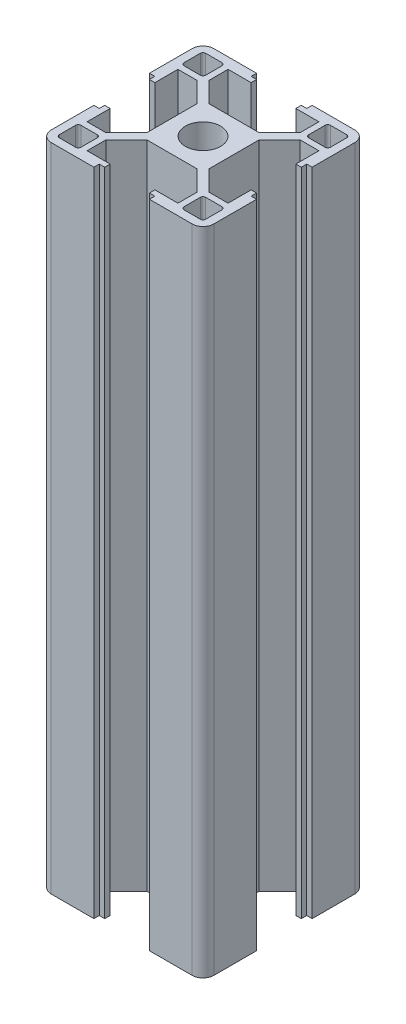
SolidWorks part; units mm, degrees
material "6061 Alloy"
ref_plane "Front Plane" through (0, 0, 0) normal (0, 0, 1) x (1, 0, 0)
ref_plane "Top Plane" through (0, 0, 0) normal (0, 1, 0) x (1, 0, 0)
ref_plane "Right Plane" through (0, 0, 0) normal (1, 0, 0) x (0, 0, -1)
sketch "Sketch1" plane through (0, 0, 0) normal (0, 1, 0) x (1, 0, 0)
  line L0 (-8.375, 13) -> (-4.125, 13)
  line L1 (-13, 15) -> (-4.125, 15)
  line L2 (-15, 13) -> (-15, 4.125)
  line L3 (-13, -15) -> (-4.125, -15)
  line L4 (15, 13) -> (15, 4.125)
  line L5 (-15, 15) -> (15, -15) construction
  line L6 (-15, -15) -> (15, 15) construction
  line L7 (-11.5, 11.5) -> (11.5, 11.5) construction
  line L8 (-11.5, 11.5) -> (-11.5, -11.5) construction
  line L9 (-11.5, -11.5) -> (11.5, -11.5) construction
  line L10 (11.5, 11.5) -> (11.5, -11.5) construction
  line L11 (-11.5, 11.5) -> (11.5, -11.5) construction
  line L12 (-11.5, -11.5) -> (11.5, 11.5) construction
  line L13 (-13.5, 13.5) -> (-9.5, 13.5)
  line L14 (-13.5, 13.5) -> (-13.5, 9.5)
  line L15 (-13.5, 9.5) -> (-9.5, 9.5)
  line L16 (-9.5, 13.5) -> (-9.5, 9.5)
  line L17 (-13.5, 13.5) -> (-9.5, 9.5) construction
  line L18 (-13.5, 9.5) -> (-9.5, 13.5) construction
  line L19 (13.5, 13.5) -> (9.5, 13.5)
  line L20 (13.5, 13.5) -> (13.5, 9.5)
  line L21 (13.5, 9.5) -> (9.5, 9.5)
  line L22 (9.5, 13.5) -> (9.5, 9.5)
  line L23 (13.5, 13.5) -> (9.5, 9.5) construction
  line L24 (13.5, 9.5) -> (9.5, 13.5) construction
  line L25 (13.5, -13.5) -> (9.5, -13.5)
  line L26 (13.5, -13.5) -> (13.5, -9.5)
  line L27 (13.5, -9.5) -> (9.5, -9.5)
  line L28 (9.5, -13.5) -> (9.5, -9.5)
  line L29 (13.5, -13.5) -> (9.5, -9.5) construction
  line L30 (13.5, -9.5) -> (9.5, -13.5) construction
  line L31 (-13.5, -13.5) -> (-9.5, -13.5)
  line L32 (-13.5, -13.5) -> (-13.5, -9.5)
  line L33 (-13.5, -9.5) -> (-9.5, -9.5)
  line L34 (-9.5, -13.5) -> (-9.5, -9.5)
  line L35 (-13.5, -13.5) -> (-9.5, -9.5) construction
  line L36 (-13.5, -9.5) -> (-9.5, -13.5) construction
  line L37 (0, 15) -> (0, 13) construction
  line L38 (-4.125, 15) -> (-4.125, 13)
  line L39 (4.125, 15) -> (4.125, 13)
  line L40 (4.125, 15) -> (13, 15)
  line L41 (-15, 15) -> (15, 15) construction
  line L42 (4.125, 13) -> (8.375, 13)
  line L43 (-15, 13) -> (15, 13) construction
  line L44 (8.375, 9.5064) -> (4.6186, 5.75)
  line L45 (-4.6186, -5.75) -> (4.6186, -5.75)
  line L46 (-8.375, 13) -> (-8.375, 9.5)
  line L47 (8.375, 13) -> (8.375, 9.5)
  line L48 (-8.375, 15) -> (-8.375, 13) construction
  line L49 (8.375, 15) -> (8.375, 13) construction
  line L50 (-5.75, -4.6186) -> (-5.75, 4.6186)
  line L51 (-4.6186, 5.75) -> (4.6186, 5.75)
  line L52 (5.75, -4.6186) -> (5.75, 4.6186)
  line L53 (-5.75, -5.75) -> (5.75, 5.75) construction
  line L54 (-5.75, 5.75) -> (5.75, -5.75) construction
  line L55 (-8.375, 9.5064) -> (-4.6186, 5.75)
  line L56 (-10.6314, 9.5) -> (-5.75, 4.6186)
  line L57 (-14.4343, 15.5657) -> (15.5657, -14.4343) construction
  line L58 (15, 4.125) -> (13, 4.125)
  line L59 (13, 8.375) -> (13, 4.125)
  line L60 (13, 8.375) -> (9.5, 8.375)
  line L61 (9.5064, 8.375) -> (5.75, 4.6186)
  line L62 (9.5064, -8.375) -> (5.75, -4.6186)
  line L63 (13, -8.375) -> (9.5, -8.375)
  line L64 (13, -4.125) -> (13, -8.375)
  line L65 (15, -4.125) -> (13, -4.125)
  line L66 (4.125, -15) -> (4.125, -13)
  line L67 (8.375, -13) -> (4.125, -13)
  line L68 (8.375, -13) -> (8.375, -9.5)
  line L69 (8.375, -9.5064) -> (4.6186, -5.75)
  line L70 (-8.375, -9.5064) -> (-4.6186, -5.75)
  line L71 (-8.375, -13) -> (-8.375, -9.5)
  line L72 (-4.125, -13) -> (-8.375, -13)
  line L73 (-4.125, -15) -> (-4.125, -13)
  line L74 (-15, -4.125) -> (-13, -4.125)
  line L75 (-13, -8.375) -> (-13, -4.125)
  line L76 (-13, -8.375) -> (-9.5, -8.375)
  line L77 (-9.5064, -8.375) -> (-5.75, -4.6186)
  line L78 (-9.5064, 8.375) -> (-5.75, 4.6186)
  line L79 (-13, 8.375) -> (-9.5, 8.375)
  line L80 (-13, 4.125) -> (-13, 8.375)
  line L81 (-15, 4.125) -> (-13, 4.125)
  line L82 (-15, -4.125) -> (-15, -13)
  line L83 (4.125, -15) -> (13, -15)
  line L84 (15, -4.125) -> (15, -13)
  circle A0 centre (0, 0) radius 3.25
  circle A1 centre (0, 0) radius 3.25
  circle A2 centre (0, 0) radius 3.25
  circle A3 centre (0, 0) radius 3.25
  arc A4 (-15, -13) -> (-13, -15) centre (-13, -13) ccw
  arc A5 (13, -15) -> (15, -13) centre (13, -13) ccw
  arc A6 (13, 15) -> (15, 13) centre (13, 13) cw
  arc A7 (-13, 15) -> (-15, 13) centre (-13, 13) ccw
  point P0 (0, 0)
  point P6 (0, 0)
  point P31 (0, 0)
  point P48 (-15.5657, 14.4343)
  point P49 (14.4343, -15.5657)
  point P60 (0, 5.75)
  point P102 (0, 0)
  dimension "D17" = 6.5
  dimension "D10" = 2
  dimension "D1" = 30
  dimension "D2" = 30
  dimension "D3" = 23
  dimension "D4" = 23
  dimension "D5" = 4
  dimension "D6" = 4
  dimension "D7" = 4
  dimension "D8" = 4
  dimension "D12" = 3.5
  dimension "D16" = 11.5
  dimension "D11" = 11.5
  dimension "D9" = 2
  dimension "D18" = 0.8
extrude "Boss-Extrude1" add sketch "Sketch1" along normal blind 120
sketch "Sketch2" plane through (0, 120, 0) normal (0, 1, 0) x (1, 0, 0)
  line L0 (15, 4.125) -> (14, 4.125)
  line L1 (-4.125, 15) -> (-5.125, 15)
  line L2 (-4.125, 15) -> (-4.125, 14)
  line L3 (-4.125, 14) -> (-5.125, 14)
  line L4 (-5.125, 15) -> (-5.125, 14)
  line L5 (4.125, 15) -> (5.125, 15)
  line L6 (4.125, 15) -> (4.125, 14)
  line L7 (4.125, 14) -> (5.125, 14)
  line L8 (5.125, 15) -> (5.125, 14)
  line L9 (15, 4.125) -> (15, 5.125)
  line L10 (15, 5.125) -> (14, 5.125)
  line L11 (14, 4.125) -> (14, 5.125)
  line L12 (15, -4.125) -> (14, -4.125)
  line L13 (15, -4.125) -> (15, -5.125)
  line L14 (15, -5.125) -> (14, -5.125)
  line L15 (14, -4.125) -> (14, -5.125)
  line L16 (4.125, -15) -> (4.125, -14)
  line L17 (4.125, -15) -> (5.125, -15)
  line L18 (5.125, -15) -> (5.125, -14)
  line L19 (4.125, -14) -> (5.125, -14)
  line L20 (-4.125, -15) -> (-4.125, -14)
  line L21 (-4.125, -15) -> (-5.125, -15)
  line L22 (-5.125, -15) -> (-5.125, -14)
  line L23 (-4.125, -14) -> (-5.125, -14)
  line L24 (-15, -4.125) -> (-14, -4.125)
  line L25 (-15, -4.125) -> (-15, -5.125)
  line L26 (-15, -5.125) -> (-14, -5.125)
  line L27 (-14, -4.125) -> (-14, -5.125)
  line L28 (-15, 4.125) -> (-14, 4.125)
  line L29 (-15, 4.125) -> (-15, 5.125)
  line L30 (-15, 5.125) -> (-14, 5.125)
  line L31 (-14, 4.125) -> (-14, 5.125)
  point P36 (0, 0)
  dimension "D1" = 1
  dimension "D2" = 1
  dimension "D3" = 1
  dimension "D4" = 1
  dimension "D5" = 4
extrude "Cut-Extrude1" cut sketch "Sketch2" against normal through all
fillet "Fillet1" radius 0.5 16 edges at (9.5, 60, 13.5) (-13.5, 60, 13.5) (-13.5, 60, -9.5) (9.5, 60, -9.5) (-13.5, 60, 9.5) (9.5, 60, 9.5) (9.5, 60, -13.5) (-13.5, 60, -13.5) (-9.5, 60, -13.5) (13.5, 60, -13.5) (13.5, 60, 9.5) (-9.5, 60, 9.5) (13.5, 60, 13.5) (-9.5, 60, 13.5) (-9.5, 60, -9.5) (13.5, 60, -9.5)
sketch "Sketch3" plane through (0, 0, -15) normal (0, 0, -1) x (-1, 0, 0)
  line L2 (-15, 120) -> (-15, 0) construction
  line L11 (-15, 51.9615) -> (-15, 0)
  line L12 (-15, 0) -> (15, 0)
  line L13 (15, 0) -> (-15, 51.9615)
  line L14 (-15, 60) -> (15, 60) construction
  line L15 (15, 120) -> (15, 0) construction
  line L27 (0, 94.0192) -> (0, 120)
  line L28 (0, 120) -> (15, 120)
  line L29 (15, 120) -> (0, 94.0192)
  line L30 (-5.125, 120) -> (-13, 120) construction
  line L31 (0, 94.0192) -> (-15, 102.6795)
  line L32 (-15, 102.6795) -> (-15, 120)
  line L33 (-15, 120) -> (0, 120)
  dimension "D1" = 30
  dimension "D2" = 60
  dimension "D3" = 30
  dimension "D4" = 90
extrude "Cut-Extrude2" [suppressed] cut sketch "Sketch3" against normal through all
equation "\"L\"= 385"
